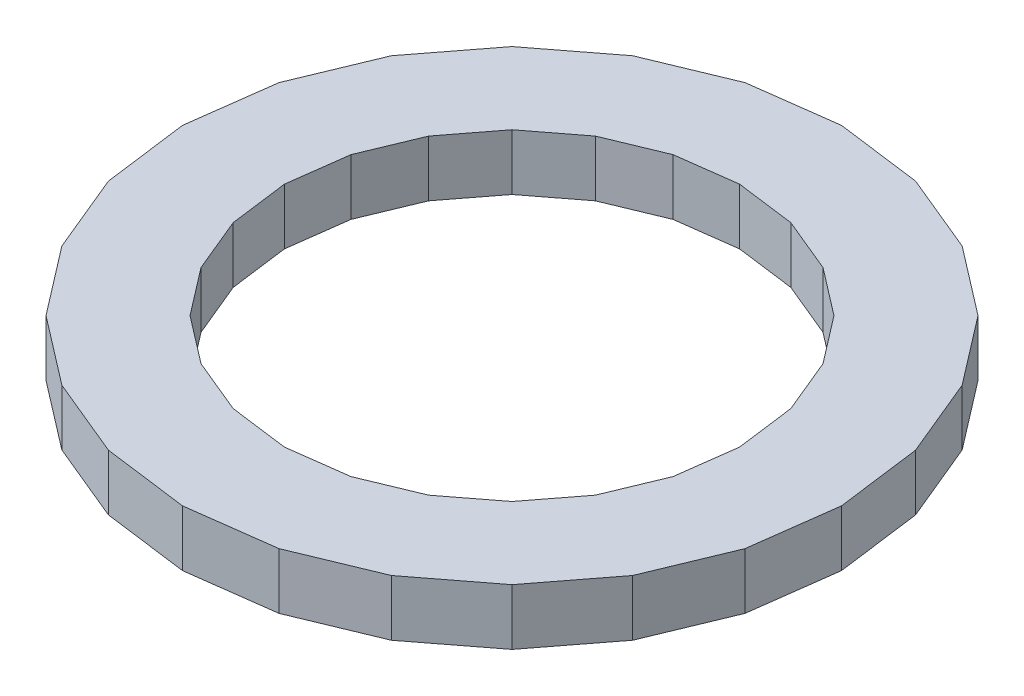
SolidWorks part; units mm, degrees
ref_plane "Front Plane" through (0, 0, 0) normal (0, 0, 1) x (1, 0, 0)
ref_plane "Top Plane" through (0, 0, 0) normal (0, 1, 0) x (1, 0, 0)
ref_plane "Right Plane" through (0, 0, 0) normal (1, 0, 0) x (0, 0, -1)
sketch "Sketch1" plane through (0, 0, 0) normal (0, 1, 0) x (1, 0, 0)
  line L0 (0, 0) -> (-77.3074, 0) construction
  line L1 (77.3074, 0) -> (74.6732, 20.0086)
  line L2 (74.6732, 20.0086) -> (66.9501, 38.6537)
  line L3 (66.9501, 38.6537) -> (54.6646, 54.6646)
  line L4 (54.6646, 54.6646) -> (38.6537, 66.9501)
  line L5 (38.6537, 66.9501) -> (20.0086, 74.6732)
  line L6 (20.0086, 74.6732) -> (0, 77.3074)
  line L7 (0, 77.3074) -> (-20.0086, 74.6732)
  line L8 (-20.0086, 74.6732) -> (-38.6537, 66.9501)
  line L9 (-38.6537, 66.9501) -> (-54.6646, 54.6646)
  line L10 (-54.6646, 54.6646) -> (-66.9501, 38.6537)
  line L11 (-66.9501, 38.6537) -> (-74.6732, 20.0086)
  line L12 (-74.6732, 20.0086) -> (-77.3074, 0)
  line L13 (-77.3074, 0) -> (-74.6732, -20.0086)
  line L14 (-74.6732, -20.0086) -> (-66.9501, -38.6537)
  line L15 (-66.9501, -38.6537) -> (-54.6646, -54.6646)
  line L16 (-54.6646, -54.6646) -> (-38.6537, -66.9501)
  line L17 (-38.6537, -66.9501) -> (-20.0086, -74.6732)
  line L18 (-20.0086, -74.6732) -> (0, -77.3074)
  line L19 (0, -77.3074) -> (20.0086, -74.6732)
  line L20 (20.0086, -74.6732) -> (38.6537, -66.9501)
  line L21 (38.6537, -66.9501) -> (54.6646, -54.6646)
  line L22 (54.6646, -54.6646) -> (66.9501, -38.6537)
  line L23 (66.9501, -38.6537) -> (74.6732, -20.0086)
  line L24 (74.6732, -20.0086) -> (77.3074, 0)
  line L25 (-111.8933, 0) -> (-108.0806, -28.9601)
  line L26 (-108.0806, -28.9601) -> (-96.9024, -55.9466)
  line L27 (-96.9024, -55.9466) -> (-79.1205, -79.1205)
  line L28 (-79.1205, -79.1205) -> (-55.9466, -96.9024)
  line L29 (-55.9466, -96.9024) -> (-28.9601, -108.0806)
  line L30 (-28.9601, -108.0806) -> (0, -111.8933)
  line L31 (0, -111.8933) -> (28.9601, -108.0806)
  line L32 (28.9601, -108.0806) -> (55.9466, -96.9024)
  line L33 (55.9466, -96.9024) -> (79.1205, -79.1205)
  line L34 (79.1205, -79.1205) -> (96.9024, -55.9466)
  line L35 (96.9024, -55.9466) -> (108.0806, -28.9601)
  line L36 (108.0806, -28.9601) -> (111.8933, 0)
  line L37 (111.8933, 0) -> (108.0806, 28.9601)
  line L38 (108.0806, 28.9601) -> (96.9024, 55.9466)
  line L39 (96.9024, 55.9466) -> (79.1205, 79.1205)
  line L40 (79.1205, 79.1205) -> (55.9466, 96.9024)
  line L41 (55.9466, 96.9024) -> (28.9601, 108.0806)
  line L42 (28.9601, 108.0806) -> (0, 111.8933)
  line L43 (0, 111.8933) -> (-28.9601, 108.0806)
  line L44 (-28.9601, 108.0806) -> (-55.9466, 96.9024)
  line L45 (-55.9466, 96.9024) -> (-79.1205, 79.1205)
  line L46 (-79.1205, 79.1205) -> (-96.9024, 55.9466)
  line L47 (-96.9024, 55.9466) -> (-108.0806, 28.9601)
  line L48 (-108.0806, 28.9601) -> (-111.8933, 0)
  line L49 (-111.8933, 0) -> (-77.3074, 0) construction
  circle A0 centre (0, 0) radius 76.646 construction
  circle A1 centre (0, 0) radius 110.936 construction
  dimension "D1" = 34.29
  dimension "D2" = 29.21
extrude "Boss-Extrude1" add sketch "Sketch1" along normal blind 19.05
